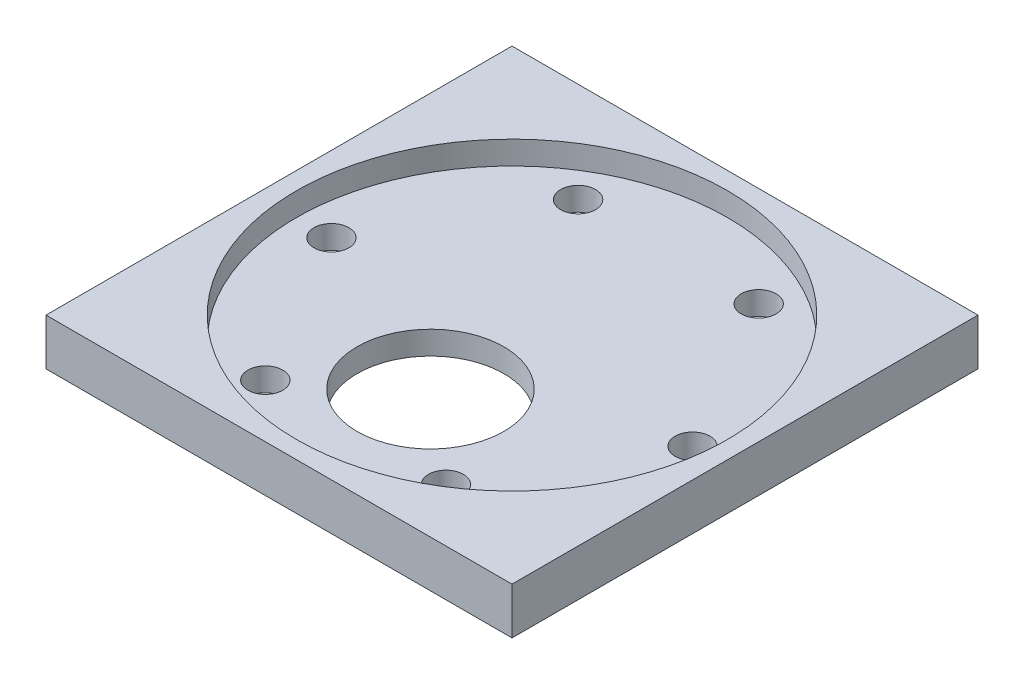
SolidWorks part; units mm, degrees
ref_plane "Front" through (0, 0, 0) normal (0, 0, 1) x (1, 0, 0)
ref_plane "Top" through (0, 0, 0) normal (0, 1, 0) x (1, 0, 0)
ref_plane "Right" through (0, 0, 0) normal (1, 0, 0) x (0, 0, -1)
sketch "Sketch1" plane through (0, 0, 0) normal (0, 1, 0) x (1, 0, 0)
  line L0 (20, -20) -> (-20, 20) construction
  line L1 (-20, 20) -> (20, 20)
  line L2 (-20, 20) -> (-20, -20)
  line L3 (-20, -20) -> (20, -20)
  line L4 (20, 20) -> (20, -20)
  point P4 (-22.0483, 10.8982)
  dimension "D1" = 40
extrude "Boss-Extrude1" add sketch "Sketch1" along normal blind 4
sketch "Sketch2" plane through (0, 4, 0) normal (0, 1, 0) x (1, 0, 0)
  line L1 (0, 0) -> (0, -18.5) construction
  line L2 (-15.5, 0) -> (15.5, 0) construction
  line L3 (7.75, 13.4234) -> (-7.75, -13.4234) construction
  line L4 (-7.75, 13.4234) -> (7.75, -13.4234) construction
  circle A0 centre (0, 0) radius 18.5 construction
  circle A1 centre (0, -7) radius 6.3
  circle A2 centre (15.5, 0) radius 1.5
  circle A3 centre (7.75, -13.4234) radius 1.5
  circle A4 centre (-7.75, -13.4234) radius 1.5
  circle A5 centre (-15.5, 0) radius 1.5
  circle A6 centre (-7.75, 13.4234) radius 1.5
  circle A7 centre (7.75, 13.4234) radius 1.5
  point P7 (-15.5, 0)
  point P9 (-15.5, 0)
  point P21 (0, 0)
  dimension "D1" = 37
  dimension "D2" = 7
  dimension "D3" = 12.6
  dimension "D4" = 3
  dimension "D5" = 31
  dimension "D6" = 6
extrude "Cut-Extrude2" cut sketch "Sketch2" against normal blind 5
sketch "Sketch3" plane through (0, 4, 0) normal (0, 1, 0) x (1, 0, 0)
  circle A0 centre (0, 0) radius 18.5
  dimension "D1" = 37
extrude "Cut-Extrude3" cut sketch "Sketch3" against normal blind 2
